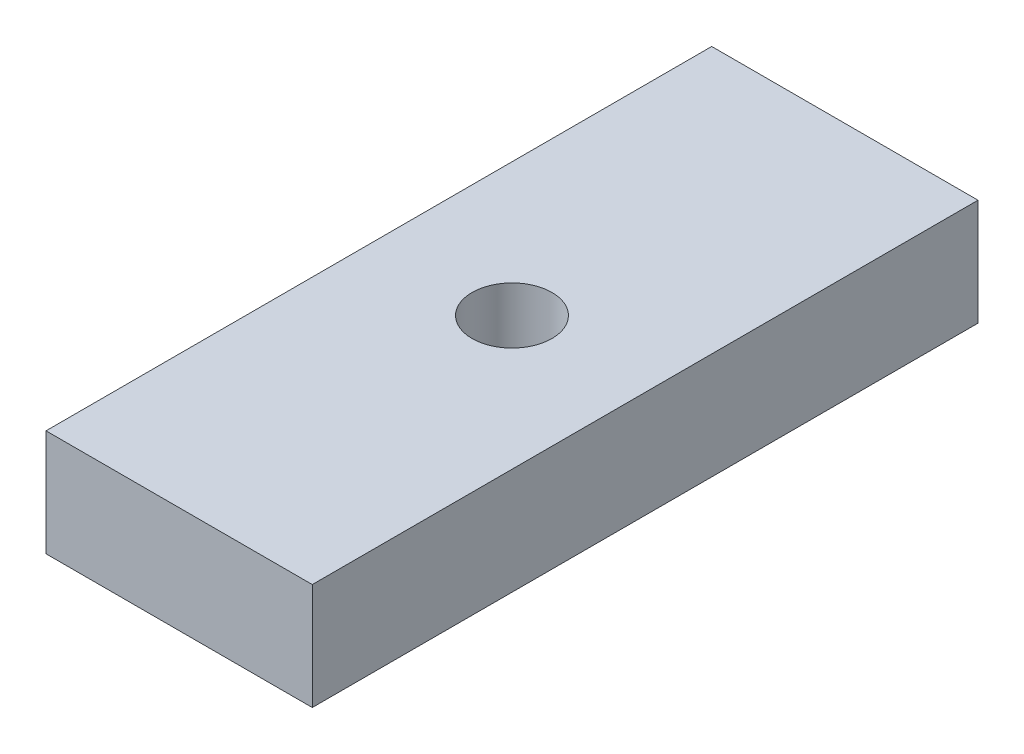
SolidWorks part; units mm, degrees
ref_plane "Front Plane" through (0, 0, 0) normal (0, 0, 1) x (1, 0, 0)
ref_plane "Top Plane" through (0, 0, 0) normal (0, 1, 0) x (1, 0, 0)
ref_plane "Right Plane" through (0, 0, 0) normal (1, 0, 0) x (0, 0, -1)
sketch "Sketch2" plane through (0, 0, 0) normal (1, 0, 0) x (0, 0, -1)
  line L0 (0, 0) -> (25, 0)
  line L4 (25, 4) -> (0, 4)
  line L7 (0, 4) -> (0, 0)
  line L8 (25, 0) -> (25, 4)
  dimension "D2" = 4
  dimension "D3" = 25
extrude "ProfileBoss-Extrude1" add sketch "Sketch2" along normal blind 10
sketch "MountHolesSketch5" plane through (0, 4, 0) normal (0, 1, 0) x (1, 0, 0)
  line L0 (0, 25) -> (0, 0) construction
  line L3 (10, 0) -> (0, 0) construction
  circle A0 centre (5, 12.5) radius 1.5
  dimension "D1" = 3
  dimension "D2" = 5
  dimension "D4" = 12.5
extrude "MountHolesCut-Extrude2" cut sketch "MountHolesSketch5" against normal through all
equation "\"ChannelRiserHeight\"= 4mm"
equation "\"D2@Sketch2\"=\"ChannelRiserHeight\""
equation "\"ChannelWidth\"= 25mm"
equation "\"ChannelLength\"= 10mm"
equation "\"D1@ProfileBoss-Extrude1\"=\"ChannelLength\""
equation "\"D3@Sketch2\"=\"ChannelWidth\""
equation "\"D4@MountHolesSketch5\"=\"ChannelWidth\"/2"
equation "\"D2@MountHolesSketch5\"=\"ChannelLength\"/2"
